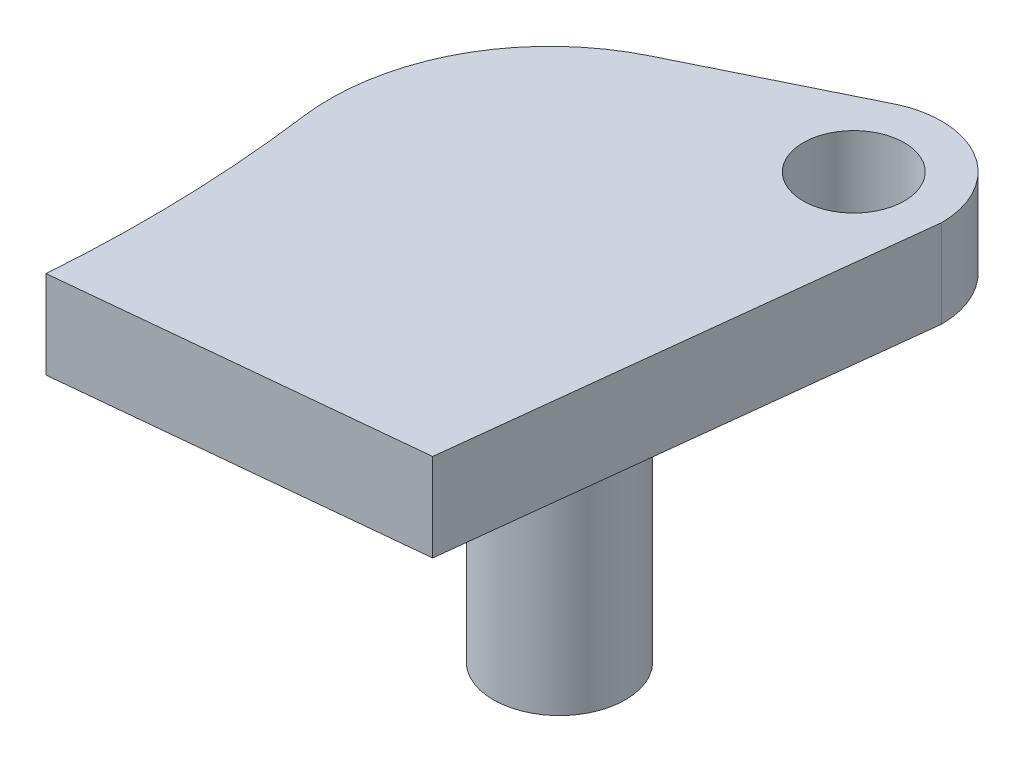
SolidWorks part; units mm, degrees
ref_plane "Front Plane" through (0, 0, 0) normal (0, 0, 1) x (1, 0, 0)
ref_plane "Top Plane" through (0, 0, 0) normal (0, 1, 0) x (1, 0, 0)
ref_plane "Right Plane" through (0, 0, 0) normal (1, 0, 0) x (0, 0, -1)
sketch "Sketch2" plane through (0, 0, 0) normal (0, 1, 0) x (1, 0, 0)
  line L1 (12.0004, 5.4685) -> (13.1829, 15.8647)
  line L5 (10.3348, 17.676) -> (3.1548, 14.1479)
  line L10 (12.0004, 5.4685) -> (4.0004, 4.673)
  circle A1 centre (11.1829, 15.8647) radius 2
  circle A2 centre (11.1829, 15.8647) radius 1.15
  arc A4 (4.0004, 4.673) -> (3.1548, 14.1479) centre (-24.9156, 6.8676) ccw
  point P5 (0, 0)
  dimension "D1" = 4
  dimension "D2" = 8
  dimension "D3" = 8
  dimension "D4" = 2.3
extrude "Boss-Extrude1" add sketch "Sketch2" along normal blind 2
sketch "Sketch3" plane through (0, 0, 0) normal (0, 1, 0) x (1, 0, 0)
  line L2 (12.0004, 5.4685) -> (13.1829, 15.8647) construction
  circle A0 centre (10.4876, 9.8647) radius 1.5
  circle A2 centre (11.1829, 15.8647) radius 1.15 construction
  dimension "D2" = 3
  dimension "D1" = 6
  dimension "D3" = 2
extrude "Boss-Extrude2" add sketch "Sketch3" against normal blind 5
fillet "Fillet1" radius 5 1 edges at (3.1548, 1, -14.1479)
